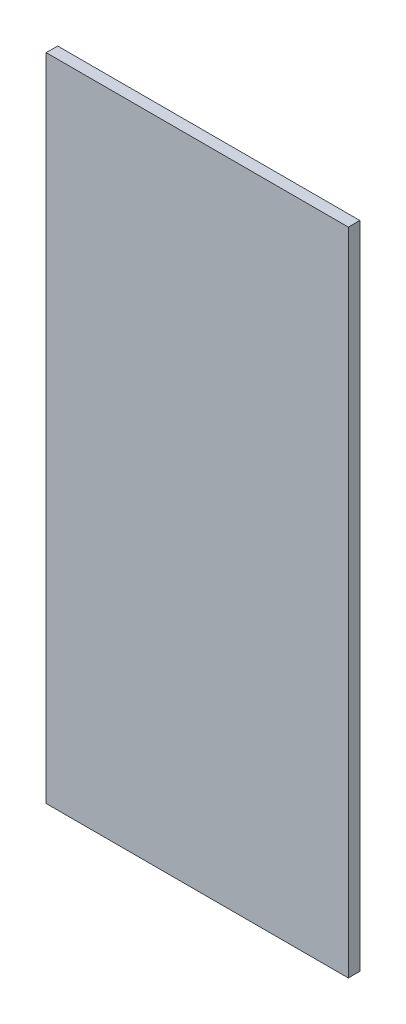
SolidWorks part; units mm, degrees
ref_plane "Front Plane" through (0, 0, 0) normal (0, 0, 1) x (1, 0, 0)
ref_plane "Top Plane" through (0, 0, 0) normal (0, 1, 0) x (1, 0, 0)
ref_plane "Right Plane" through (0, 0, 0) normal (1, 0, 0) x (0, 0, -1)
sketch "Sketch2" plane through (0, 0, 0) normal (0, 0, 1) x (1, 0, 0)
  line L1 (-13.15, -28.3) -> (13.15, -28.3)
  line L2 (-13.15, -28.3) -> (-13.15, 28.3)
  line L3 (-13.15, 28.3) -> (13.15, 28.3)
  line L4 (13.15, -28.3) -> (13.15, 28.3)
  line L5 (-13.15, -28.3) -> (13.15, 28.3) construction
  line L6 (-13.15, 28.3) -> (13.15, -28.3) construction
  point P0 (0, 0)
  dimension "D1" = 56.6
  dimension "D2" = 26.3
extrude "Boss-Extrude1" add sketch "Sketch2" along normal blind 1
